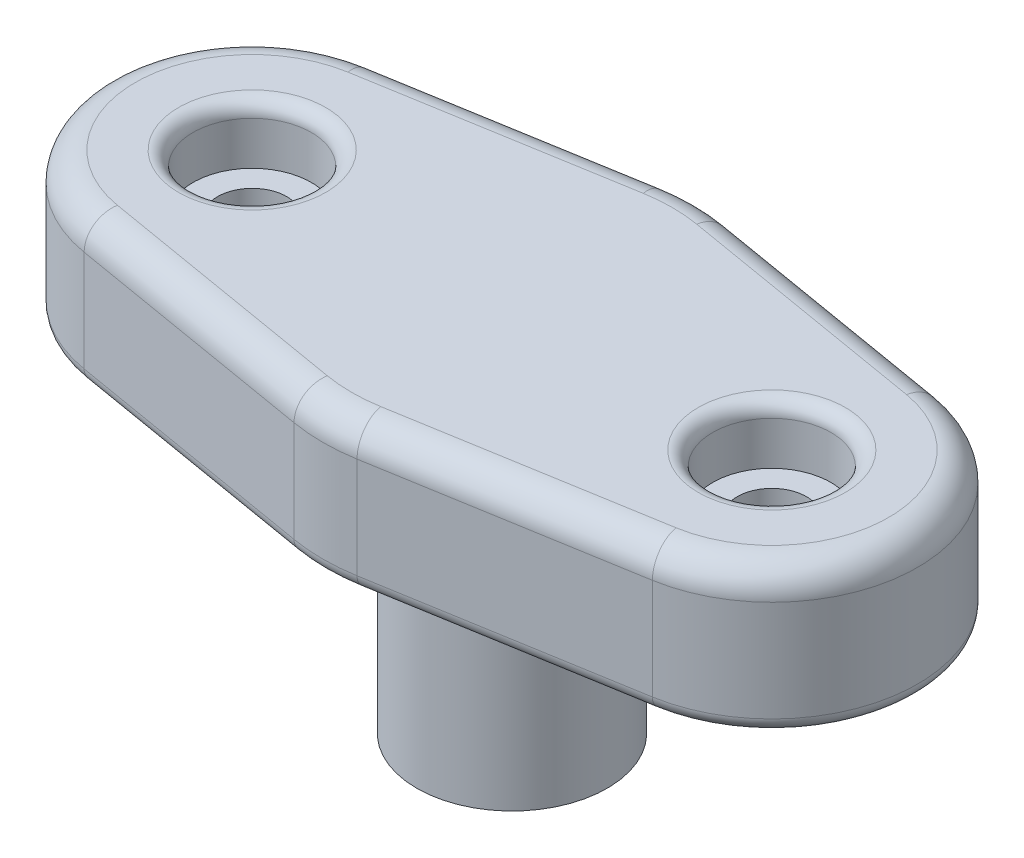
SolidWorks part; units mm, degrees
ref_plane "Front Plane" through (0, 0, 0) normal (0, 0, 1) x (1, 0, 0)
ref_plane "Top Plane" through (0, 0, 0) normal (0, 1, 0) x (1, 0, 0)
ref_plane "Right Plane" through (0, 0, 0) normal (1, 0, 0) x (0, 0, -1)
sketch "Sketch1" plane through (0, 0, 0) normal (0, 1, 0) x (1, 0, 0)
  circle A0 centre (0, 0) radius 3.3
  dimension "D1" = 6.6
extrude "Boss-Extrude1" add sketch "Sketch1" along normal blind 8
sketch "Sketch2" plane through (0, 8, 0) normal (0, 1, 0) x (1, 0, 0)
  line L0 (-9, 0) -> (9, 0) construction
  line L1 (-9.8417, 4.9794) -> (-1.0917, 6.4584)
  line L4 (9.8417, -4.9794) -> (1.0917, -6.4584)
  line L5 (1.0917, 6.4584) -> (9.8417, 4.9794)
  line L6 (-1.0917, -6.4584) -> (-9.8417, -4.9794)
  circle A0 centre (-9, 0) radius 1.2
  circle A1 centre (9, 0) radius 1.2
  arc A2 (-9.8417, 4.9794) -> (-9.8417, -4.9794) centre (-9, 0) ccw
  arc A3 (9.8417, -4.9794) -> (9.8417, 4.9794) centre (9, 0) ccw
  arc A4 (-1.0917, -6.4584) -> (1.0917, -6.4584) centre (0, 0) ccw
  arc A5 (1.0917, 6.4584) -> (-1.0917, 6.4584) centre (0, 0) ccw
  point P4 (0, 0)
  point P6 (10.0383, 1.8253)
  point P7 (0, 0)
  point P9 (0, 0)
  point P17 (11.9314, -0.6899)
  dimension "D1" = 2.4
  dimension "D2" = 2.4
  dimension "D4" = 10.1
  dimension "D5" = 10.1
  dimension "D6" = 13.1
  dimension "D3" = 18
extrude "Boss-Extrude2" add sketch "Sketch2" along normal blind 5
sketch "Sketch3" plane through (0, 13, 0) normal (0, 1, 0) x (1, 0, 0)
  circle A0 centre (-9, 0) radius 2.05
  circle A1 centre (9, 0) radius 2.05
  dimension "D1" = 4.1
  dimension "D2" = 4.1
extrude "Cut-Extrude1" cut sketch "Sketch3" against normal blind 2
fillet "Fillet1" radius 0.5 10 edges at (-14.05, 8, 0) (-5.4667, 8, -5.7189) (0, 8, -6.55) (5.4667, 8, -5.7189) (14.05, 8, 0) (5.4667, 8, 5.7189) (0, 8, 6.55) (-5.4667, 8, 5.7189) (9, 13, 2.05) (-9, 13, 2.05)
fillet "Fillet2" radius 1 8 edges at (-5.4667, 13, -5.7189) (0, 13, -6.55) (5.4667, 13, -5.7189) (14.05, 13, 0) (5.4667, 13, 5.7189) (0, 13, 6.55) (-5.4667, 13, 5.7189) (-14.05, 13, 0)
